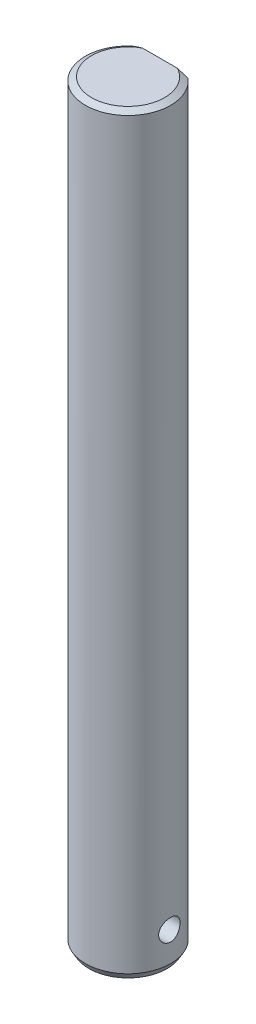
SolidWorks part; units mm, degrees
ref_plane "Front Plane" through (0, 0, 0) normal (0, 0, 1) x (1, 0, 0)
ref_plane "Top Plane" through (0, 0, 0) normal (0, 1, 0) x (1, 0, 0)
ref_plane "Right Plane" through (0, 0, 0) normal (1, 0, 0) x (0, 0, -1)
sketch "Sketch1" plane through (0, 0, 0) normal (0, 1, 0) x (1, 0, 0)
  circle A0 centre (0, 0) radius 6
  dimension "D1" = 12
extrude "Boss-Extrude1" add sketch "Sketch1" along normal blind 106
sketch "Sketch2" plane through (0, 106, 0) normal (0, 1, 0) x (1, 0, 0)
  line L1 (-5.4013, 8.821) -> (5.0226, 8.821)
  line L2 (-5.4013, 8.821) -> (-5.4013, 4.5)
  line L3 (-5.4013, 4.5) -> (5.0226, 4.5)
  line L4 (5.0226, 8.821) -> (5.0226, 4.5)
  dimension "D1" = 4.5
extrude "Cut-Extrude1" cut sketch "Sketch2" against normal blind 10
sketch "Sketch3" plane through (0, 0, 0) normal (1, 0, 0) x (0, 0, -1)
  circle A0 centre (0, 5) radius 1.5
  point P2 (0, 0)
  dimension "D1" = 3
  dimension "D2" = 5
extrude "Cut-Extrude2" cut sketch "Sketch3" against normal mid plane 40
chamfer "Chamfer1" distance 0.5 angle 60 2 edges at (0, 106, 6) (0, 0, 6)
